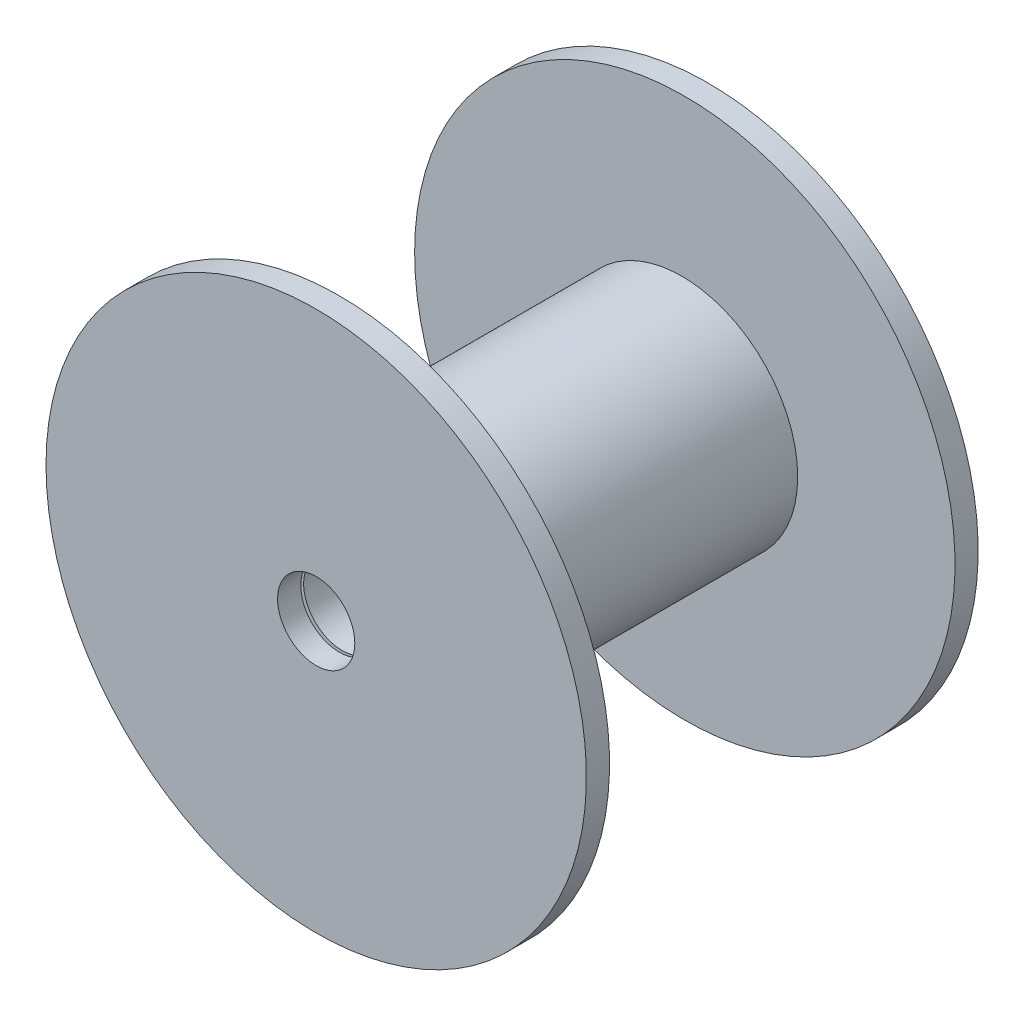
SolidWorks part; units mm, degrees
ref_plane "Plan de face" through (0, 0, 0) normal (0, 0, 1) x (1, 0, 0)
ref_plane "Plan de dessus" through (0, 0, 0) normal (0, 1, 0) x (1, 0, 0)
ref_plane "Plan de droite" through (0, 0, 0) normal (1, 0, 0) x (0, 0, -1)
sketch "Esquisse1" plane through (0, 0, 0) normal (0, 0, 1) x (1, 0, 0)
  circle A0 centre (0, 0) radius 5
  circle A1 centre (0, 0) radius 15
  circle A2 centre (0, 0) radius 35
  dimension "D1" = 10
  dimension "D2" = 30
  dimension "D3" = 70
extrude "Boss.-Extru.1" add sketch "Esquisse1" along normal blind 44 contours A1 A0
sketch "Esquisse2" plane through (0, 0, 0) normal (1, 0, 0) x (0, 0, -1)
  line L0 (-44, 0) -> (0, 0) construction
  line L1 (-44, 15) -> (-44, -15) construction
  line L2 (-22, 0) -> (-22, 17.2818) construction
  line L3 (-53.225, 0) -> (-44, 0) construction
  line L4 (-44.3747, 35) -> (-47.3747, 35)
  line L5 (-44.3747, 35) -> (-44.3747, 0)
  line L6 (-44.3747, 0) -> (-47.3747, 0)
  line L7 (-47.3747, 35) -> (-47.3747, 0)
  line L8 (0.3747, 0) -> (3.3747, 0)
  line L9 (3.3747, 35) -> (3.3747, 0)
  line L10 (0.3747, 35) -> (3.3747, 35)
  line L11 (0.3747, 35) -> (0.3747, 0)
  dimension "D1" = 35
  dimension "D2" = 3
  dimension "D3" = 35
revolve "Révolution3" add sketch "Esquisse2" angle 360 about L6
sketch "Esquisse3" plane through (0, 0, 0) normal (0, 0, 1) x (1, 0, 0)
  circle A0 centre (0, 0) radius 5
  dimension "D1" = 10
extrude "Enlèv. mat.-Extru.2" cut sketch "Esquisse3" along normal blind 64 and the other way blind 0.3747 contours A0
sketch "Esquisse5" plane through (0, 0, -3.3747) normal (0, 0, -1) x (-1, 0, 0)
  circle A0 centre (0, 0) radius 5
  dimension "D1" = 10
extrude "Enlèv. mat.-Extru.3" cut sketch "Esquisse5" against normal through all
